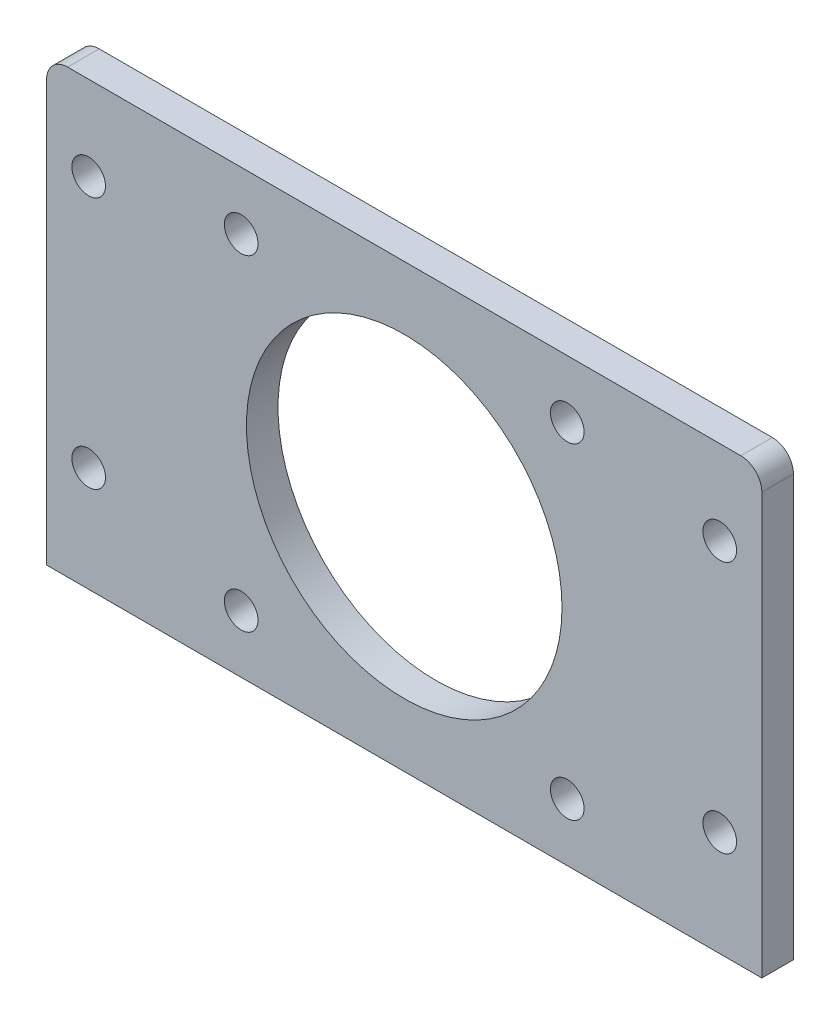
SolidWorks part; units mm, degrees
ref_plane "前视基准面" through (0, 0, 0) normal (0, 0, 1) x (1, 0, 0)
ref_plane "上视基准面" through (0, 0, 0) normal (0, 1, 0) x (1, 0, 0)
ref_plane "右视基准面" through (0, 0, 0) normal (1, 0, 0) x (0, 0, -1)
other "Configuration Table"
sketch "草图1" plane through (0, 0, 0) normal (0, 0, 1) x (1, 0, 0)
  line L0 (-34, 0) -> (34, 0)
  line L1 (-34, 0) -> (-34, 40)
  line L2 (-32, 42) -> (32, 42)
  line L3 (34, 40) -> (34, 0)
  line L4 (-15.5, 5.5) -> (15.5, 5.5) construction
  line L5 (-30, 34) -> (30, 34) construction
  circle A0 centre (15.5, 5.5) radius 1.6
  circle A1 centre (-15.5, 5.5) radius 1.6
  circle A2 centre (-15.5, 36.5) radius 1.6
  circle A3 centre (15.5, 36.5) radius 1.6
  circle A4 centre (30, 34) radius 1.6
  circle A5 centre (30, 10) radius 1.6
  circle A6 centre (-30, 10) radius 1.6
  circle A7 centre (-30, 34) radius 1.6
  arc A8 (32, 42) -> (34, 40) centre (32, 40) cw
  arc A9 (-34, 40) -> (-32, 42) centre (-32, 40) cw
  circle A10 centre (0, 21) radius 15
  point P2 (0, 0)
  point P8 (0, 5.5)
  point P25 (0, 34)
  point P31 (34, 42)
  point P34 (-34, 42)
  dimension "D3" = 3.2
  dimension "D10" = 3.2
  dimension "D11" = 2
  dimension "D13" = 30
  dimension "D1" = 5.5
  dimension "D2" = 31
  dimension "D4" = 31
  dimension "D5" = 31
  dimension "D6" = 42
  dimension "D7" = 68
  dimension "D8" = 8
  dimension "D9" = 10
  dimension "D12" = 15.5
  dimension "55" = 60
extrude "凸台-拉伸1" add sketch "草图1" along normal blind 3
